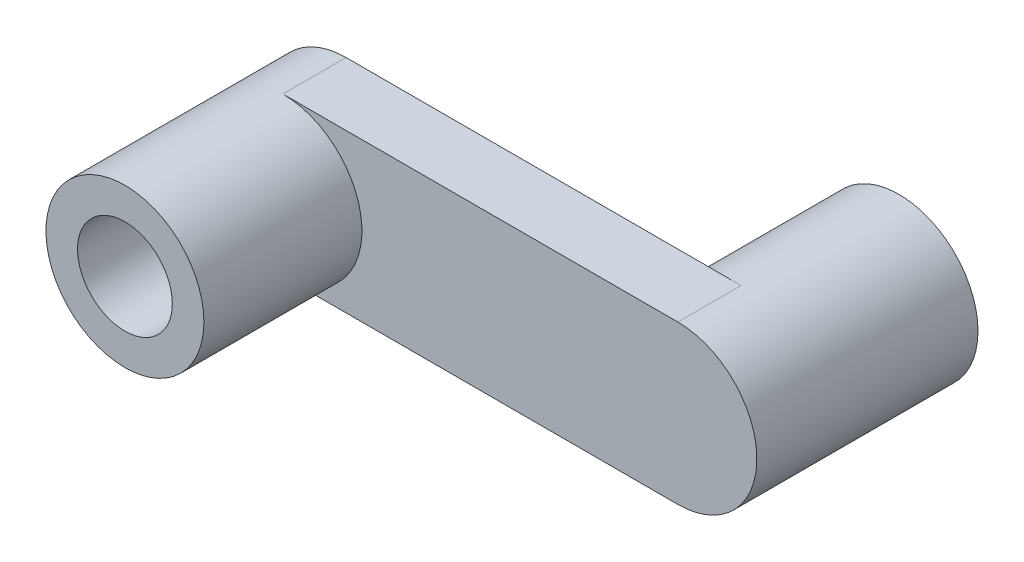
SolidWorks part; units mm, degrees
ref_plane "Front Plane" through (0, 0, 0) normal (0, 0, 1) x (1, 0, 0)
ref_plane "Top Plane" through (0, 0, 0) normal (0, 1, 0) x (1, 0, 0)
ref_plane "Right Plane" through (0, 0, 0) normal (1, 0, 0) x (0, 0, -1)
sketch "Sketch2" plane through (0, 0, 0) normal (0, 0, 1) x (1, 0, 0)
  line L0 (-20.9818, 0) -> (29.4909, 0) construction
  line L1 (-17.0545, 5) -> (7.9455, 5)
  line L2 (-17.0545, -5) -> (7.9455, -5)
  arc A0 (-17.0545, 5) -> (-17.0545, -5) centre (-17.0545, 0) ccw
  arc A1 (7.9455, -5) -> (7.9455, 5) centre (7.9455, 0) ccw
  dimension "D1" = 25
  dimension "D2" = 25
  dimension "D3" = 5
  dimension "D4" = 5
extrude "Boss-Extrude1" add sketch "Sketch2" along normal mid plane 4
sketch "Sketch3" plane through (0, 0, 2) normal (0, 0, 1) x (1, 0, 0)
  circle A0 centre (-17.0545, 0) radius 5
  circle A1 centre (-17.0545, 0) radius 3
  arc A2 (-17.0545, 5) -> (-17.0545, -5) centre (-17.0545, 0) ccw construction
  dimension "D1" = 6
extrude "Boss-Extrude2" add sketch "Sketch3" along normal blind 10
sketch "Sketch4" plane through (0, 0, -2) normal (0, 0, -1) x (-1, 0, 0)
  circle A0 centre (-7.9455, 0) radius 5
  circle A1 centre (-7.9455, 0) radius 3
  arc A2 (-7.9455, 5) -> (-7.9455, -5) centre (-7.9455, 0) ccw construction
  dimension "D1" = 6
extrude "Boss-Extrude3" add sketch "Sketch4" along normal blind 10
